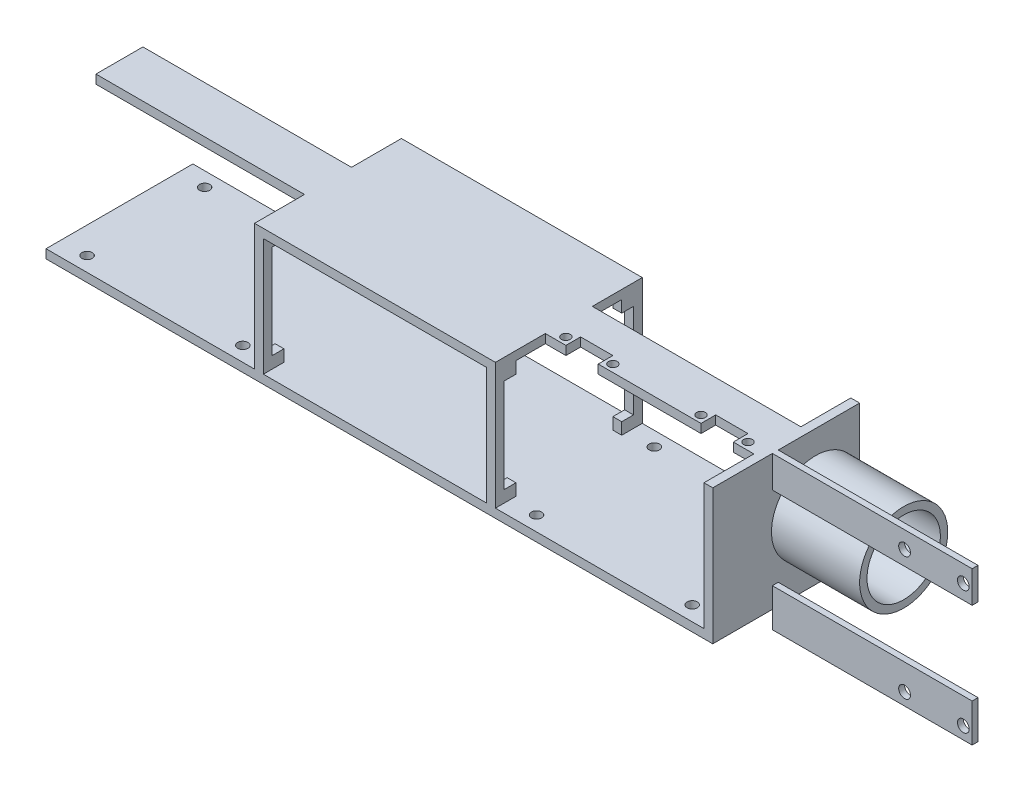
SolidWorks part; units mm, degrees
ref_plane "Front Plane" through (0, 0, 0) normal (0, 0, 1) x (1, 0, 0)
ref_plane "Top Plane" through (0, 0, 0) normal (0, 1, 0) x (1, 0, 0)
ref_plane "Right Plane" through (0, 0, 0) normal (1, 0, 0) x (0, 0, -1)
sketch "Sketch1" plane through (0, 0, 0) normal (0, 0, 1) x (1, 0, 0)
  line L1 (-41, -23) -> (41, -23)
  line L2 (-41, -23) -> (-41, 23)
  line L3 (-41, 23) -> (41, 23)
  line L4 (41, -23) -> (41, 23)
  line L5 (-41, -23) -> (41, 23) construction
  line L6 (-41, 23) -> (41, -23) construction
  point P0 (0, 0)
  dimension "D1" = 82
  dimension "D2" = 46
extrude "Boss-Extrude1" add sketch "Sketch1" along normal mid plane 50
sketch "Sketch2" plane through (0, 0, 25) normal (0, 0, 1) x (1, 0, 0)
  line L0 (41, 23) -> (-41, 23) construction
  line L1 (-38, 20) -> (38, 20)
  line L2 (-38, 20) -> (-38, -20)
  line L3 (-38, -20) -> (38, -20)
  line L4 (38, 20) -> (38, -20)
  line L5 (-38, 20) -> (38, -20) construction
  line L6 (-38, -20) -> (38, 20) construction
  line L7 (-41, 23) -> (-41, -23) construction
  point P0 (0, 0)
  dimension "D1" = 3
  dimension "D2" = 3
extrude "Cut-Extrude1" cut sketch "Sketch2" against normal up to next
sketch "Sketch3" plane through (-41, 0, 0) normal (-1, 0, 0) x (0, 0, 1)
  line L0 (-18, 16) -> (-18, 20)
  line L1 (-18, 20) -> (18, 20)
  line L2 (18, 20) -> (18, 16)
  line L3 (18, 16) -> (22, 16)
  line L4 (22, 16) -> (22, -16)
  line L5 (22, -16) -> (18, -16)
  line L6 (18, -16) -> (18, -20)
  line L7 (18, -20) -> (-18, -20)
  line L8 (-18, -20) -> (-18, -16)
  line L9 (-18, -16) -> (-22, -16)
  line L10 (-22, -16) -> (-22, 16)
  line L11 (-22, 16) -> (-18, 16)
  line L12 (25, 23) -> (-25, 23) construction
  line L13 (-25, 23) -> (-25, -23) construction
  line L14 (25, 23) -> (25, -23) construction
  line L15 (25, -23) -> (-25, -23) construction
  dimension "D1" = 3
  dimension "D2" = 3
  dimension "D3" = 3
  dimension "D4" = 3
  dimension "D5" = 7
  dimension "D6" = 7
  dimension "D7" = 7
  dimension "D8" = 7
  dimension "D9" = 7
  dimension "D10" = 7
  dimension "D11" = 7
  dimension "D12" = 7
extrude "Cut-Extrude2" cut sketch "Sketch3" against normal through all both and the other way through all
sketch "Sketch4" plane through (41, 0, 0) normal (1, 0, 0) x (0, 0, -1)
  line L0 (25, -23) -> (25, 23) construction
  line L1 (-25, -23) -> (25, -23)
  line L2 (-25, -23) -> (-25, -20)
  line L3 (-25, -20) -> (25, -20)
  line L4 (25, -23) -> (25, -20)
  dimension "D1" = 3
extrude "Boss-Extrude2" add sketch "Sketch4" along normal blind 71
sketch "Sketch5" plane through (0, -20, 0) normal (0, 1, 0) x (1, 0, 0)
  line L2 (112, -25) -> (41, -25) construction
  line L3 (41, -18) -> (41, -25) construction
  line L4 (41, 25) -> (41, 18) construction
  circle A0 centre (103.1, 20.1) radius 1.75
  circle A1 centre (103, -20) radius 1.75
  circle A2 centre (50, 20.1) radius 1.75
  circle A3 centre (50, -20) radius 1.75
  point P8 (0, 0)
  dimension "D1" = 3.5
  dimension "D2" = 3.5
  dimension "D3" = 3.5
  dimension "D4" = 3.5
  dimension "D5" = 53
  dimension "D6" = 53.1
  dimension "D7" = 9
  dimension "D8" = 9
  dimension "D9" = 40.1
  dimension "D10" = 40.1
  dimension "D11" = 5
  dimension "D12" = 5
extrude "Cut-Extrude3" cut sketch "Sketch5" against normal up to next
sketch "Sketch6" plane through (41, 0, 0) normal (1, 0, 0) x (0, 0, -1)
  line L1 (-25, 23) -> (-18, 23)
  line L2 (-25, 23) -> (-25, 16)
  line L3 (-25, 16) -> (-18, 16)
  line L4 (-18, 23) -> (-18, 16)
  line L5 (25, 23) -> (18, 23)
  line L6 (25, 23) -> (25, 16)
  line L7 (25, 16) -> (18, 16)
  line L8 (18, 23) -> (18, 16)
  point P10 (-18, 19.5)
  dimension "D1" = 7
  dimension "D2" = 7
  dimension "D3" = 7
  dimension "D4" = 7
sketch "Sketch7" plane through (41, 0, 0) normal (1, 0, 0) x (0, 0, -1)
  line L0 (-25, 23) -> (25, 23) construction
  line L1 (-8, 23) -> (8, 23)
  line L2 (-8, 23) -> (-8, 20)
  line L3 (-8, 20) -> (8, 20)
  line L4 (8, 23) -> (8, 20)
  line L5 (-18, 20) -> (18, 20) construction
  line L6 (-25, 23) -> (-25, 16) construction
  dimension "D1" = 16
  dimension "D2" = 17
extrude "Boss-Extrude4" add sketch "Sketch7" along normal blind 71
sketch "Sketch8" plane through (112, 0, 0) normal (1, 0, 0) x (0, 0, -1)
  line L1 (-25, -23) -> (25, -23)
  line L2 (-25, -23) -> (-25, 23)
  line L3 (-25, 23) -> (25, 23)
  line L4 (25, -23) -> (25, 23)
  dimension "D1" = 46
  dimension "D2" = 50
extrude "Boss-Extrude5" add sketch "Sketch8" along normal blind 3
sketch "Sketch9" plane through (0, 23, 0) normal (0, 1, 0) x (1, 0, 0)
  line L0 (105, -8) -> (105, -3)
  line L1 (112, -8) -> (41, -8) construction
  line L2 (105, -3) -> (94, -3)
  line L3 (94, -3) -> (94, -8)
  line L4 (112, -8) -> (112, -25) construction
  dimension "D1" = 7
  dimension "D2" = 18
  dimension "D3" = 5
extrude "Cut-Extrude4" cut sketch "Sketch9" against normal blind 3 and the other way through all
sketch "Sketch10" plane through (0, 23, 0) normal (0, 1, 0) x (1, 0, 0)
  line L0 (48, -8) -> (48, -3)
  line L1 (94, -8) -> (41, -8) construction
  line L2 (48, -3) -> (59, -3)
  line L3 (59, -3) -> (59, -8)
  line L4 (59, -8) -> (48, -8)
  line L5 (41, -25) -> (41, -8) construction
  dimension "D1" = 5
  dimension "D2" = 11
  dimension "D3" = 7
extrude "Cut-Extrude5" cut sketch "Sketch10" against normal up to next
sketch "Sketch11" plane through (0, 23, 0) normal (0, 1, 0) x (1, 0, 0)
  line L0 (112, -8) -> (105, -8) construction
  line L1 (105, -3) -> (105, -8) construction
  line L2 (94, -8) -> (94, -3) construction
  line L3 (94, -8) -> (59, -8) construction
  line L4 (59, -8) -> (59, -3) construction
  line L5 (48, -8) -> (41, -8) construction
  line L6 (48, -3) -> (48, -8) construction
  circle A0 centre (45.5, -5.5) radius 1.5
  circle A1 centre (61.5, -5.5) radius 1.5
  circle A2 centre (91.5, -5.5) radius 1.5
  circle A3 centre (107.5, -5.5) radius 1.5
  dimension "D1" = 3
  dimension "D2" = 3
  dimension "D3" = 3
  dimension "D4" = 3
  dimension "D5" = 2.5
  dimension "D6" = 2.5
  dimension "D7" = 2.5
  dimension "D8" = 2.5
  dimension "D9" = 2.5
  dimension "D10" = 2.5
  dimension "D11" = 2.5
  dimension "D12" = 2.5
extrude "Cut-Extrude6" cut sketch "Sketch11" against normal up to next
sketch "Sketch12" plane through (115, 0, 0) normal (1, 0, 0) x (0, 0, -1)
  line L0 (25, -23) -> (25, 23) construction
  circle A0 centre (10, 0) radius 15
  dimension "D1" = 30
  dimension "D2" = 15
extrude "Boss-Extrude6" add sketch "Sketch12" along normal blind 30
sketch "Sketch13" plane through (145, 0, 0) normal (1, 0, 0) x (0, 0, -1)
  line L0 (25, -23) -> (25, 0) construction
  circle A0 centre (10, 0) radius 12.5
  dimension "D1" = 25
  dimension "D2" = 15
extrude "Cut-Extrude7" cut sketch "Sketch13" against normal through all
sketch "Sketch14" plane through (115, 0, 0) normal (1, 0, 0) x (0, 0, -1)
  line L0 (25, 23) -> (-25, 23) construction
  line L1 (-4.7, 23) -> (-2.7, 23)
  line L2 (-4.7, 23) -> (-4.7, 12.2)
  line L3 (-4.7, 12.2) -> (-2.7, 12.2)
  line L4 (-2.7, 23) -> (-2.7, 12.2)
  line L10 (-25, 23) -> (-25, 16) construction
  line L11 (-25, 23) -> (-25, -23) construction
  line L12 (-4.7, -16) -> (-2.7, -16)
  line L13 (-4.7, -16) -> (-4.7, -29)
  line L14 (-4.7, -29) -> (-2.7, -29)
  line L15 (-2.7, -16) -> (-2.7, -29)
  line L16 (-25, -23) -> (25, -23) construction
  dimension "D1" = 10.8
  dimension "D2" = 22.3
  dimension "D3" = 2
  dimension "D4" = 13
  dimension "D5" = 22.3
  dimension "D6" = 2
  dimension "D7" = 7
extrude "Boss-Extrude7" add sketch "Sketch14" along normal blind 68
sketch "Sketch15" plane through (0, 0, 2.7) normal (0, 0, -1) x (-1, 0, 0)
  circle A0 centre (-180, -24.8) radius 2
  circle A1 centre (-160, -24.8) radius 2
  circle A2 centre (-160, 17.2) radius 2
  circle A3 centre (-180, 17.2) radius 2
  dimension "D1" = 4
  dimension "D2" = 4
  dimension "D3" = 4
  dimension "D4" = 4
extrude "Cut-Extrude8" cut sketch "Sketch15" against normal up to next
mirror "Mirror1" about plane through (0, 0, 0) normal (1, 0, 0) of "Boss-Extrude4", "Cut-Extrude3", "Boss-Extrude2"
